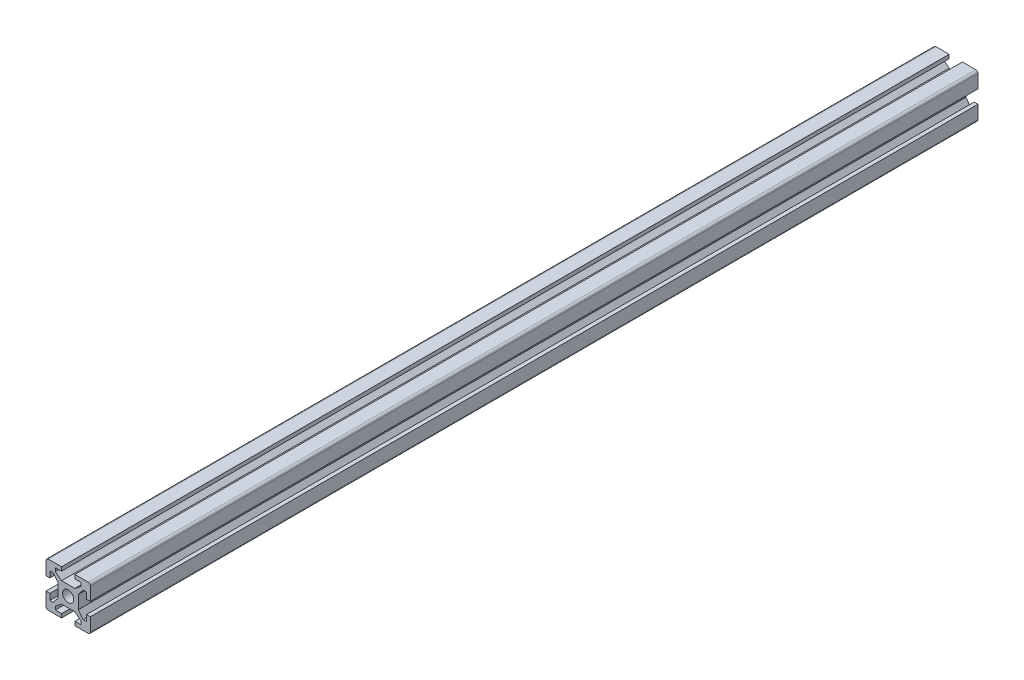
SolidWorks part; units mm, degrees
ref_plane "Front Plane" through (0, 0, 0) normal (0, 0, 1) x (1, 0, 0)
ref_plane "Top Plane" through (0, 0, 0) normal (0, 1, 0) x (1, 0, 0)
ref_plane "Right Plane" through (0, 0, 0) normal (1, 0, 0) x (0, 0, -1)
sketch "Sketch1" plane through (0, 0, 0) normal (0, 0, 1) x (1, 0, 0)
  line L18 (0, 0) -> (0, 20.5117) construction
  line L39 (-10, 10) -> (-3, 10)
  line L41 (10, 10) -> (3, 10)
  line L43 (-10, 10) -> (-10, 3)
  line L45 (-10, -10) -> (-10, -3)
  line L47 (-10, -10) -> (-3, -10)
  line L49 (3, -10) -> (10, -10)
  line L51 (10, -10) -> (10, -3)
  line L53 (10, 3) -> (10, 10)
  line L55 (-3, 10) -> (-3, 8.2726)
  line L56 (-3, 8.2726) -> (-5.7838, 8.2726)
  line L57 (-5.7838, 8.2726) -> (-5.7838, 6.748)
  line L58 (-5.7838, 6.748) -> (-3, 4.5508)
  line L59 (-3, 4.5508) -> (3, 4.5508)
  line L60 (3, 10) -> (3, 8.2726)
  line L61 (3, 8.2726) -> (5.7838, 8.2726)
  line L62 (5.7838, 8.2726) -> (5.7838, 6.748)
  line L63 (5.7838, 6.748) -> (3, 4.5508)
  line L64 (10, 3) -> (8.2726, 3)
  line L65 (8.2726, 3) -> (8.2726, 5.7838)
  line L66 (8.2726, 5.7838) -> (6.748, 5.7838)
  line L67 (10, -3) -> (8.2726, -3)
  line L68 (8.2726, -3) -> (8.2726, -5.7838)
  line L69 (8.2726, -5.7838) -> (6.748, -5.7838)
  line L70 (4.55, -2.9994) -> (4.55, 3.0006)
  line L71 (4.55, -2.9994) -> (6.748, -5.7838)
  line L72 (4.55, 3.0006) -> (6.748, 5.7838)
  line L73 (3, -10) -> (3, -8.2726)
  line L74 (3, -8.2726) -> (5.7838, -8.2726)
  line L75 (5.7838, -8.2726) -> (5.7838, -6.748)
  line L76 (-3, -10) -> (-3, -8.2726)
  line L77 (-3, -8.2726) -> (-5.7838, -8.2726)
  line L78 (-5.7838, -8.2726) -> (-5.7838, -6.748)
  line L79 (2.9994, -4.55) -> (-3.0006, -4.55)
  line L80 (5.7838, -6.748) -> (2.9994, -4.55)
  line L81 (-5.7838, -6.748) -> (-3.0006, -4.55)
  line L82 (-10, -3) -> (-8.2726, -3)
  line L83 (-8.2726, -3) -> (-8.2726, -5.7838)
  line L84 (-8.2726, -5.7838) -> (-6.748, -5.7838)
  line L85 (-10, 3) -> (-8.2726, 3)
  line L86 (-8.2726, 3) -> (-8.2726, 5.7838)
  line L87 (-8.2726, 5.7838) -> (-6.748, 5.7838)
  line L88 (-4.55, -3.0006) -> (-4.55, 2.9994)
  line L89 (-6.748, -5.7838) -> (-4.55, -3.0006)
  line L90 (-4.55, 2.9994) -> (-6.748, 5.7838)
  dimension "D9" = 7
  dimension "D17" = 2.7838
  dimension "D1" = 20
  dimension "D2" = 20
  dimension "D3" = 10
  dimension "D4" = 10
  dimension "D5" = 7
  dimension "D6" = 7
  dimension "D7" = 7
  dimension "D8" = 7
  dimension "D10" = 7
  dimension "D11" = 7
  dimension "D12" = 7
  dimension "D13" = 6
  dimension "D14" = 3
  dimension "D15" = 3.5464
  dimension "D16" = 1.5246
  dimension "D18" = 1.7274
  dimension "D19" = 4.55
  dimension "D20" = 4.55
  dimension "D21" = 4.55
  dimension "D22" = 10
  dimension "D23" = 10
  dimension "D24" = 10
  dimension "D25" = 10
  dimension "D26" = 10
  dimension "D27" = 10
  dimension "D28" = 6
  dimension "D29" = 6
  dimension "D30" = 6
  dimension "D31" = 6
extrude "Boss-Extrude1" add sketch "Sketch1" along normal mid plane 400
sketch "Sketch2" plane through (0, 0, 200) normal (0, 0, 1) x (1, 0, 0)
  circle A0 centre (0, 0) radius 2.5
  dimension "D1" = 5
extrude "Cut-Extrude1" cut sketch "Sketch2" against normal through all both and the other way through all
fillet "Fillet1" radius 1 4 edges at (-10, -10, 0) (10, -10, 0) (10, 10, 0) (-10, 10, 0)
